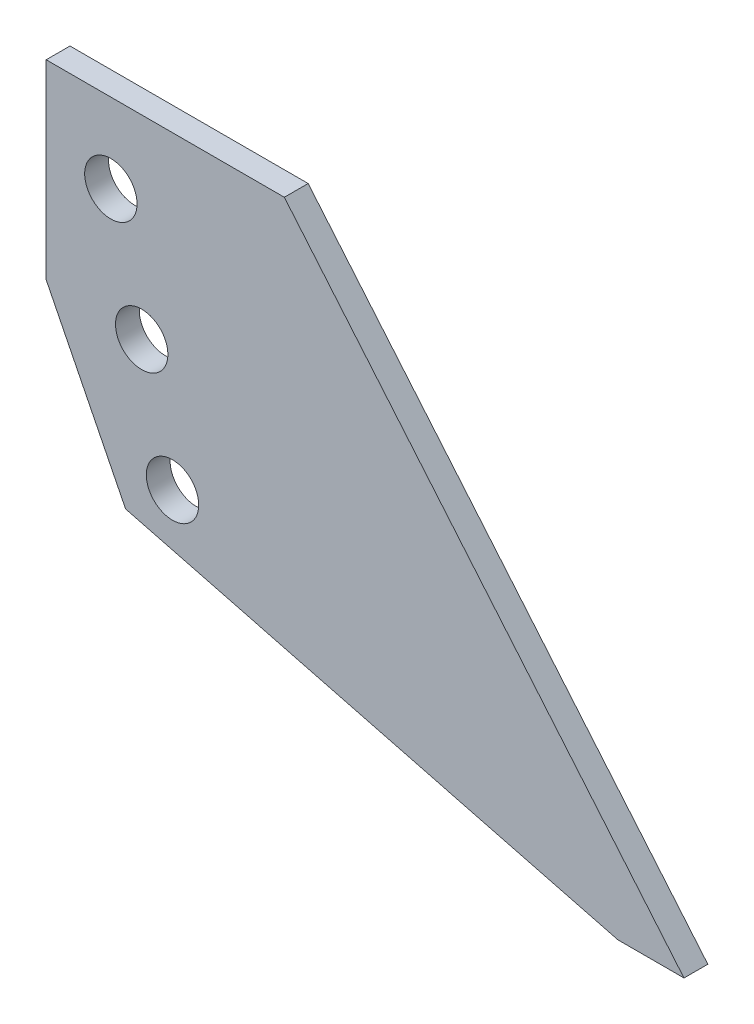
SolidWorks part; units mm, degrees
material "AISI 4340 Aço, normalizado"
ref_plane "Plano frontal" through (0, 0, 0) normal (0, 0, 1) x (1, 0, 0)
ref_plane "Plano superior" through (0, 0, 0) normal (0, 1, 0) x (1, 0, 0)
ref_plane "Plano direito" through (0, 0, 0) normal (1, 0, 0) x (0, 0, -1)
sketch "Esboço1" plane through (0, 0, 0) normal (0, 0, 1) x (1, 0, 0)
  line L0 (0, 0) -> (0, 60)
  line L1 (0, 60) -> (30, 60)
  line L4 (80.346, 0) -> (0, 0)
  line L5 (30, 60) -> (80.346, 0)
  dimension "D1" = 50
  dimension "D3" = 30
  dimension "D4" = 60
extrude "Ressalto-extrusão1" add sketch "Esboço1" along normal blind 3
hole_wizard "Furo com folga de M61" positions "Esboço2" profile "Esboço3" hole size "M6" standard "ISO" end condition through all
sketch "Esboço2" plane through (0, 0, 3) normal (0, 0, 1) x (1, 0, 0)
  point P0 (15.9131, 21.0222)
  point P3 (12.0309, 35.5111)
  point P6 (8.1486, 50)
sketch "Esboço3" plane through (15.9131, 21.0222, 3) normal (1, 0, 0) x (0, -1, 0)
  line L0 (0, 0) -> (0, 3)
  line L1 (0, 3) -> (3.3, 3)
  line L2 (3.3, 3) -> (3.3, 0)
  line L5 (3.3, 0) -> (0, 0)
  line L11 (0, -6.35) -> (0, 107.95) construction
  dimension "Thru Hole Dia." = 6.6
  dimension "Thru Hole Depth" = 3
sketch "Esboço4" plane through (0, 0, 3) normal (0, 0, 1) x (1, 0, 0)
  line L0 (0, 36) -> (10, 16)
  line L1 (0, 60) -> (0, 0) construction
  line L4 (0, 0) -> (0, 36)
  line L5 (10, 16) -> (72, 0)
  line L10 (0, 0) -> (80.346, 0) construction
  line L11 (0, 0) -> (72, 0)
  dimension "D1" = 72
  dimension "D2" = 36
  dimension "D3" = 20
  dimension "D4" = 62
extrude "Corte-extrusão1" cut sketch "Esboço4" against normal through all
